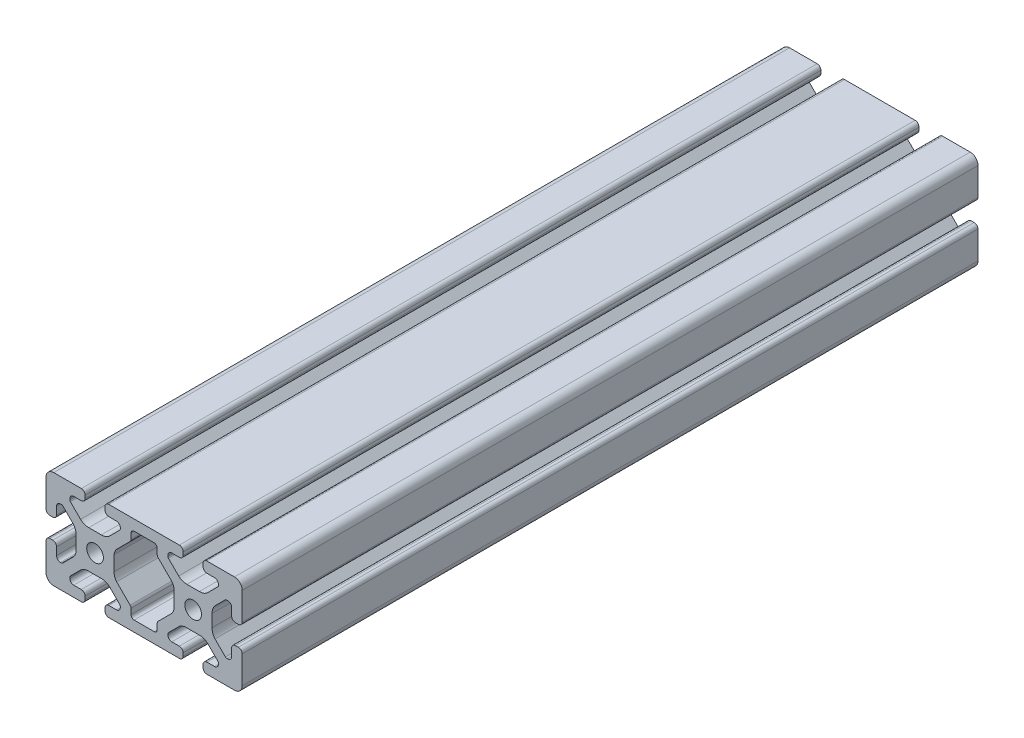
SolidWorks part; units mm, degrees
material "6105-T5 Aluminum"
ref_plane "Front Plane" through (0, 0, 0) normal (0, 0, 1) x (1, 0, 0)
ref_plane "Top Plane" through (0, 0, 0) normal (0, 1, 0) x (1, 0, 0)
ref_plane "Right Plane" through (0, 0, 0) normal (1, 0, 0) x (0, 0, -1)
sketch "Sketch1" plane through (0, 0, 0) normal (0, 0, 1) x (1, 0, 0)
  line L0 (-14.3719, 20) -> (14.3719, 20)
  line L1 (-15.94, 17.1729) -> (-15.94, 18.3529)
  line L2 (-11.285, 15.68) -> (-14.37, 15.68)
  line L3 (-9.715, 13.6545) -> (-9.715, 14.11)
  line L4 (4.0718, 15.68) -> (-4.0718, 15.68)
  line L5 (-5.3418, 14.41) -> (-5.3418, 12.1296)
  line L6 (-5.7137, 11.2316) -> (-10.5988, 6.3465)
  line L7 (-12.2841, 3.2591) -> (-12.2841, -2.725)
  line L8 (5.991, -20) -> (-1.7801, -20)
  line L9 (0, 20) -> (0, -25.1394) construction
  line L10 (-4.0718, -15.68) -> (4.0718, -15.68)
  line L11 (-5.3418, -12.1296) -> (-5.3418, -14.41)
  line L12 (-11.2012, -5.7441) -> (-5.7137, -11.2316)
  line L13 (-42.275, 0) -> (43.1806, 0) construction
  line L14 (-9.9376, 13.1171) -> (-14.0919, 8.9628)
  line L15 (-17.4506, 7.7) -> (-22.5494, 7.7)
  line L16 (-25.9081, 8.9628) -> (-30.0624, 13.1171)
  line L17 (-30.285, 13.6545) -> (-30.285, 14.11)
  line L18 (-28.715, 15.68) -> (-25.63, 15.68)
  line L19 (-24.06, 17.25) -> (-24.06, 18.4312)
  line L20 (-25.5696, 20) -> (-33, 20)
  line L21 (-33, 20) -> (-36.83, 20)
  line L22 (-40, 16.8406) -> (-40, 13.0106)
  line L23 (-40, 13.0106) -> (-40, 5.5825)
  line L24 (-38.3243, 4.06) -> (-37.1443, 4.06)
  line L25 (-35.68, 5.6264) -> (-35.68, 8.7114)
  line L26 (-34.11, 10.2814) -> (-33.6509, 10.2814)
  line L27 (-33.1135, 10.0588) -> (-29.0111, 5.9564)
  line L28 (-27.7159, 2.571) -> (-27.7159, -2.502)
  line L29 (-28.9155, -5.8608) -> (-33.1719, -10.1172)
  line L30 (-33.7093, -10.3398) -> (-34.111, -10.3398)
  line L31 (-35.68, -8.715) -> (-35.68, -5.63)
  line L32 (-37.25, -4.06) -> (-38.4312, -4.06)
  line L33 (-40, -5.5696) -> (-40, -13)
  line L34 (-40, -13) -> (-40, -16.83)
  line L35 (-37.0574, -20) -> (-33.2274, -20)
  line L36 (-33.2274, -20) -> (-25.797, -20)
  line L37 (-24.06, -18.4389) -> (-24.06, -17.25)
  line L38 (-25.63, -15.68) -> (-28.715, -15.68)
  line L39 (-30.285, -14.11) -> (-30.285, -13.6545)
  line L40 (-30.0624, -13.1171) -> (-26.3095, -9.3642)
  line L41 (-23.3415, -7.7) -> (-16.6585, -7.7)
  line L42 (-13.6905, -9.3642) -> (-9.9376, -13.1171)
  line L43 (-9.715, -13.6545) -> (-9.715, -14.11)
  line L44 (-11.285, -15.68) -> (-14.37, -15.68)
  line L45 (-15.94, -17.25) -> (-15.94, -18.43)
  line L46 (-14.37, -20) -> (-5.991, -20)
  line L47 (-5.991, -20) -> (-1.7801, -20)
  line L48 (14.37, -20) -> (5.991, -20)
  line L49 (15.94, -17.25) -> (15.94, -18.43)
  line L50 (11.285, -15.68) -> (14.37, -15.68)
  line L51 (9.715, -13.6545) -> (9.715, -14.11)
  line L52 (13.6905, -9.3642) -> (9.9376, -13.1171)
  line L53 (23.3415, -7.7) -> (16.6585, -7.7)
  line L54 (30.0624, -13.1171) -> (26.3095, -9.3642)
  line L55 (30.285, -14.11) -> (30.285, -13.6545)
  line L56 (25.63, -15.68) -> (28.715, -15.68)
  line L57 (24.06, -18.4389) -> (24.06, -17.25)
  line L58 (33.2274, -20) -> (25.797, -20)
  line L59 (37.0574, -20) -> (33.2274, -20)
  line L60 (40, -13) -> (40, -16.83)
  line L61 (40, -5.5696) -> (40, -13)
  line L62 (37.25, -4.06) -> (38.4312, -4.06)
  line L63 (35.68, -8.715) -> (35.68, -5.63)
  line L64 (33.7093, -10.3398) -> (34.111, -10.3398)
  line L65 (28.9155, -5.8608) -> (33.1719, -10.1172)
  line L66 (27.7159, 2.571) -> (27.7159, -2.502)
  line L67 (33.1135, 10.0588) -> (29.0111, 5.9564)
  line L68 (34.11, 10.2814) -> (33.6509, 10.2814)
  line L69 (35.68, 5.6264) -> (35.68, 8.7114)
  line L70 (38.3243, 4.06) -> (37.1443, 4.06)
  line L71 (40, 13.0106) -> (40, 5.5825)
  line L72 (40, 16.8406) -> (40, 13.0106)
  line L73 (33, 20) -> (36.83, 20)
  line L74 (25.5696, 20) -> (33, 20)
  line L75 (24.06, 17.25) -> (24.06, 18.4312)
  line L76 (28.715, 15.68) -> (25.63, 15.68)
  line L77 (30.285, 13.6545) -> (30.285, 14.11)
  line L78 (25.9081, 8.9628) -> (30.0624, 13.1171)
  line L79 (17.4506, 7.7) -> (22.5494, 7.7)
  line L80 (9.9376, 13.1171) -> (14.0919, 8.9628)
  line L81 (11.2012, -5.7441) -> (5.7137, -11.2316)
  line L82 (5.3418, -12.1296) -> (5.3418, -14.41)
  line L83 (12.2841, 3.2591) -> (12.2841, -2.725)
  line L84 (5.7137, 11.2316) -> (10.5988, 6.3465)
  line L85 (5.3418, 14.41) -> (5.3418, 12.1296)
  line L86 (9.715, 13.6545) -> (9.715, 14.11)
  line L87 (11.285, 15.68) -> (14.37, 15.68)
  line L88 (15.94, 17.1729) -> (15.94, 18.3529)
  line L89 (-20, 24.8708) -> (-20, -18.43) construction
  line L90 (20, 29.4355) -> (20, -23.1087) construction
  line L91 (-3.0962, 16.9038) -> (-43.6857, -23.6857) construction
  line L92 (-36.2671, 16.2671) -> (-2.7875, -17.2125) construction
  arc A0 (-15.94, 18.3529) -> (-14.3719, 20) centre (-14.3719, 18.43) cw
  circle A1 centre (-20, 0) radius 3.4
  arc A2 (-14.37, 15.68) -> (-15.94, 17.1729) centre (-14.3719, 17.25) cw
  arc A3 (-11.285, 15.68) -> (-9.715, 14.11) centre (-11.285, 14.11) cw
  arc A4 (-9.715, 13.6545) -> (-9.9376, 13.1171) centre (-10.475, 13.6545) cw
  arc A5 (-12.2841, -2.725) -> (-11.2012, -5.7441) centre (-7.5341, -2.725) ccw
  arc A6 (-4.0718, 15.68) -> (-5.3418, 14.41) centre (-4.0718, 14.41) ccw
  arc A7 (-5.7137, 11.2316) -> (-5.3418, 12.1296) centre (-6.6118, 12.1296) ccw
  arc A8 (-10.5988, 6.3465) -> (-12.2841, 3.2591) centre (-7.5685, 2.6887) ccw
  arc A9 (-5.3418, -14.41) -> (-4.0718, -15.68) centre (-4.0718, -14.41) ccw
  arc A10 (-5.3418, -12.1296) -> (-5.7137, -11.2316) centre (-6.6118, -12.1296) ccw
  arc A11 (-17.4506, 7.7) -> (-14.0919, 8.9628) centre (-17.3191, 12.4482) ccw
  arc A12 (-25.9081, 8.9628) -> (-22.5494, 7.7) centre (-22.6809, 12.4482) ccw
  arc A13 (-30.285, 13.6545) -> (-30.0624, 13.1171) centre (-29.525, 13.6545) ccw
  arc A14 (-28.715, 15.68) -> (-30.285, 14.11) centre (-28.715, 14.11) ccw
  arc A15 (-25.63, 15.68) -> (-24.06, 17.25) centre (-25.63, 17.25) ccw
  arc A16 (-24.06, 18.4312) -> (-25.5696, 20) centre (-25.63, 18.4312) ccw
  arc A17 (-36.83, 20) -> (-40, 16.8406) centre (-36.83, 16.83) ccw
  arc A18 (-40, 5.5825) -> (-38.3243, 4.06) centre (-38.4306, 5.6264) ccw
  arc A19 (-37.1443, 4.06) -> (-35.68, 5.6264) centre (-37.25, 5.6264) ccw
  arc A20 (-34.11, 10.2814) -> (-35.68, 8.7114) centre (-34.11, 8.7114) ccw
  arc A21 (-33.1135, 10.0588) -> (-33.6509, 10.2814) centre (-33.6509, 9.5214) ccw
  arc A22 (-27.7159, 2.571) -> (-29.0111, 5.9564) centre (-32.4643, 2.6948) ccw
  arc A23 (-28.9155, -5.8608) -> (-27.7159, -2.502) centre (-32.4617, -2.7006) ccw
  arc A24 (-33.7093, -10.3398) -> (-33.1719, -10.1172) centre (-33.7093, -9.5798) ccw
  arc A25 (-35.68, -8.715) -> (-34.111, -10.3398) centre (-34.111, -8.7698) ccw
  arc A26 (-35.68, -5.63) -> (-37.25, -4.06) centre (-37.25, -5.63) ccw
  arc A27 (-38.4312, -4.06) -> (-40, -5.5696) centre (-38.4312, -5.63) ccw
  arc A28 (-40, -16.83) -> (-37.0574, -20) centre (-36.83, -16.8382) ccw
  arc A29 (-25.797, -20) -> (-24.06, -18.4389) centre (-25.63, -18.4389) ccw
  arc A30 (-24.06, -17.25) -> (-25.63, -15.68) centre (-25.63, -17.25) ccw
  arc A31 (-30.285, -14.11) -> (-28.715, -15.68) centre (-28.715, -14.11) ccw
  arc A32 (-30.0624, -13.1171) -> (-30.285, -13.6545) centre (-29.525, -13.6545) ccw
  arc A33 (-23.3415, -7.7) -> (-26.3095, -9.3642) centre (-22.6565, -12.4003) ccw
  arc A34 (-13.6905, -9.3642) -> (-16.6585, -7.7) centre (-17.3435, -12.4003) ccw
  arc A35 (-9.715, -13.6545) -> (-9.9376, -13.1171) centre (-10.475, -13.6545) ccw
  arc A36 (-11.285, -15.68) -> (-9.715, -14.11) centre (-11.285, -14.11) ccw
  arc A37 (-14.37, -15.68) -> (-15.94, -17.25) centre (-14.37, -17.25) ccw
  arc A38 (-15.94, -18.43) -> (-14.37, -20) centre (-14.37, -18.43) ccw
  arc A39 (15.94, -18.43) -> (14.37, -20) centre (14.37, -18.43) cw
  arc A40 (14.37, -15.68) -> (15.94, -17.25) centre (14.37, -17.25) cw
  arc A41 (11.285, -15.68) -> (9.715, -14.11) centre (11.285, -14.11) cw
  arc A42 (9.715, -13.6545) -> (9.9376, -13.1171) centre (10.475, -13.6545) cw
  arc A43 (13.6905, -9.3642) -> (16.6585, -7.7) centre (17.3435, -12.4003) cw
  arc A44 (23.3415, -7.7) -> (26.3095, -9.3642) centre (22.6565, -12.4003) cw
  arc A45 (30.0624, -13.1171) -> (30.285, -13.6545) centre (29.525, -13.6545) cw
  arc A46 (30.285, -14.11) -> (28.715, -15.68) centre (28.715, -14.11) cw
  arc A47 (24.06, -17.25) -> (25.63, -15.68) centre (25.63, -17.25) cw
  arc A48 (25.797, -20) -> (24.06, -18.4389) centre (25.63, -18.4389) cw
  arc A49 (40, -16.83) -> (37.0574, -20) centre (36.83, -16.8382) cw
  arc A50 (38.4312, -4.06) -> (40, -5.5696) centre (38.4312, -5.63) cw
  arc A51 (35.68, -5.63) -> (37.25, -4.06) centre (37.25, -5.63) cw
  arc A52 (35.68, -8.715) -> (34.111, -10.3398) centre (34.111, -8.7698) cw
  arc A53 (33.7093, -10.3398) -> (33.1719, -10.1172) centre (33.7093, -9.5798) cw
  arc A54 (28.9155, -5.8608) -> (27.7159, -2.502) centre (32.4617, -2.7006) cw
  arc A55 (27.7159, 2.571) -> (29.0111, 5.9564) centre (32.4643, 2.6948) cw
  arc A56 (33.1135, 10.0588) -> (33.6509, 10.2814) centre (33.6509, 9.5214) cw
  arc A57 (34.11, 10.2814) -> (35.68, 8.7114) centre (34.11, 8.7114) cw
  arc A58 (37.1443, 4.06) -> (35.68, 5.6264) centre (37.25, 5.6264) cw
  arc A59 (40, 5.5825) -> (38.3243, 4.06) centre (38.4306, 5.6264) cw
  arc A60 (36.83, 20) -> (40, 16.8406) centre (36.83, 16.83) cw
  arc A61 (24.06, 18.4312) -> (25.5696, 20) centre (25.63, 18.4312) cw
  arc A62 (25.63, 15.68) -> (24.06, 17.25) centre (25.63, 17.25) cw
  arc A63 (28.715, 15.68) -> (30.285, 14.11) centre (28.715, 14.11) cw
  arc A64 (30.285, 13.6545) -> (30.0624, 13.1171) centre (29.525, 13.6545) cw
  arc A65 (25.9081, 8.9628) -> (22.5494, 7.7) centre (22.6809, 12.4482) cw
  arc A66 (17.4506, 7.7) -> (14.0919, 8.9628) centre (17.3191, 12.4482) cw
  arc A67 (5.3418, -12.1296) -> (5.7137, -11.2316) centre (6.6118, -12.1296) cw
  arc A68 (5.3418, -14.41) -> (4.0718, -15.68) centre (4.0718, -14.41) cw
  arc A69 (10.5988, 6.3465) -> (12.2841, 3.2591) centre (7.5685, 2.6887) cw
  arc A70 (5.7137, 11.2316) -> (5.3418, 12.1296) centre (6.6118, 12.1296) cw
  arc A71 (4.0718, 15.68) -> (5.3418, 14.41) centre (4.0718, 14.41) cw
  arc A72 (12.2841, -2.725) -> (11.2012, -5.7441) centre (7.5341, -2.725) cw
  arc A73 (9.715, 13.6545) -> (9.9376, 13.1171) centre (10.475, 13.6545) ccw
  arc A74 (11.285, 15.68) -> (9.715, 14.11) centre (11.285, 14.11) ccw
  arc A75 (14.37, 15.68) -> (15.94, 17.1729) centre (14.3719, 17.25) ccw
  circle A76 centre (20, 0) radius 3.4
  arc A77 (15.94, 18.3529) -> (14.3719, 20) centre (14.3719, 18.43) ccw
  dimension "D4" = 6.8
  dimension "D1" = 80
  dimension "D2" = 40
  dimension "D3" = 20
  dimension "D5" = 8.12
  dimension "D6" = 4.32
  dimension "D7" = 20.57
  dimension "D8" = 4.32
  dimension "D9" = 8.12
  dimension "D10" = 12.3
  dimension "D11" = 4.32
  dimension "D12" = 4.32
  dimension "D13" = 4.32
extrude "Extrude1" add sketch "Sketch1" against normal blind 300
